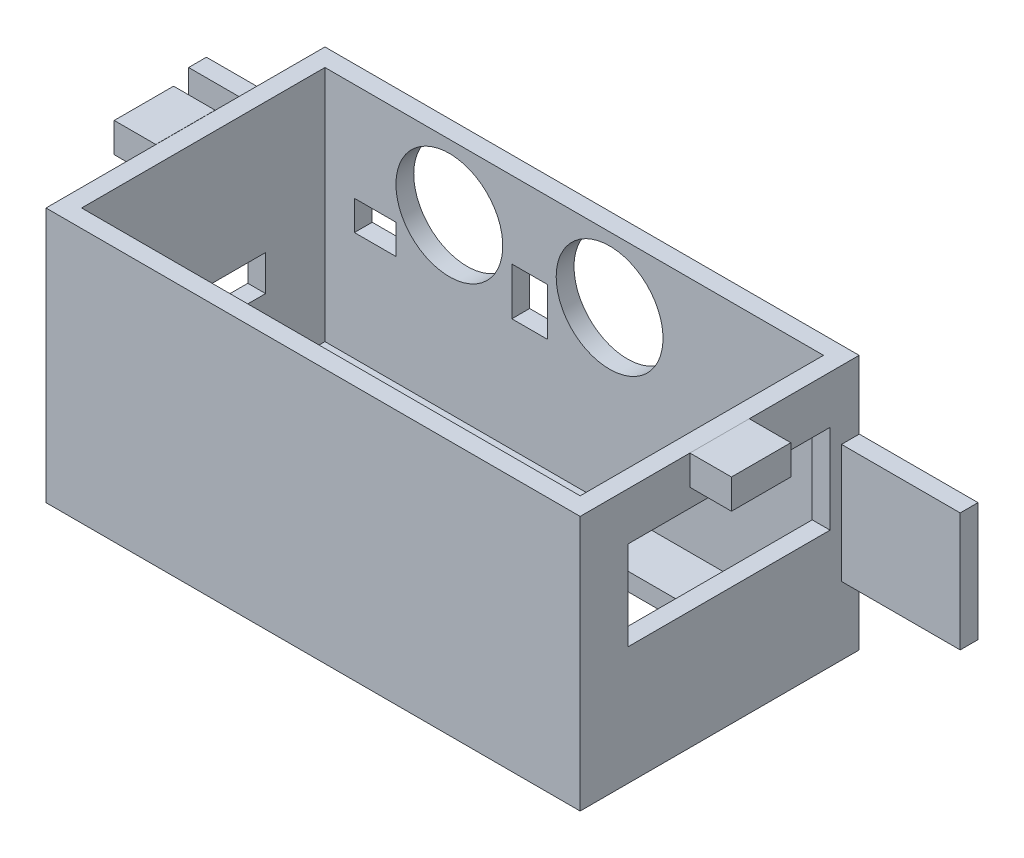
SolidWorks part; units mm, degrees
ref_plane "Alzado" through (0, 0, 0) normal (0, 0, 1) x (1, 0, 0)
ref_plane "Planta" through (0, 0, 0) normal (0, 1, 0) x (1, 0, 0)
ref_plane "Vista lateral" through (0, 0, 0) normal (1, 0, 0) x (0, 0, -1)
sketch "Croquis1" plane through (0, 0, 0) normal (0, 1, 0) x (1, 0, 0)
  line L1 (-45, 23.5) -> (45, 23.5)
  line L2 (-45, 23.5) -> (-45, -23.5)
  line L3 (-45, -23.5) -> (45, -23.5)
  line L4 (45, 23.5) -> (45, -23.5)
  line L5 (-45, 23.5) -> (45, -23.5) construction
  line L6 (-45, -23.5) -> (45, 23.5) construction
  point P0 (0, 0)
extrude "Saliente-Extruir1" add sketch "Croquis1" along normal blind 3
sketch "Croquis2" plane through (0, 3, 0) normal (0, 1, 0) x (1, 0, 0)
  line L1 (-42, 20.5) -> (42, 20.5)
  line L2 (-42, 20.5) -> (-42, -20.5)
  line L3 (-42, -20.5) -> (42, -20.5)
  line L4 (42, 20.5) -> (42, -20.5)
  line L5 (-42, 20.5) -> (42, -20.5) construction
  line L6 (-42, -20.5) -> (42, 20.5) construction
  line L9 (45, 23.5) -> (-45, 23.5) construction
  line L10 (-45, 23.5) -> (-45, -23.5) construction
  line L11 (45, -23.5) -> (45, 23.5) construction
  line L12 (-45, -23.5) -> (45, -23.5) construction
  line L13 (45, 23.5) -> (-45, 23.5)
  line L14 (-45, 23.5) -> (-45, -23.5)
  line L15 (45, -23.5) -> (45, 23.5)
  line L16 (-45, -23.5) -> (45, -23.5)
  point P0 (0, 0)
extrude "Saliente-Extruir2" add sketch "Croquis2" along normal blind 40
sketch "Croquis6" plane through (0, 0, 0) normal (0, -1, 0) x (-1, 0, 0)
  line L1 (36.0091, -12.4705) -> (-35.9909, -12.4705)
  line L2 (36.0091, -12.4705) -> (36.0091, 12.5295)
  line L3 (36.0091, 12.5295) -> (-35.9909, 12.5295)
  line L4 (-35.9909, -12.4705) -> (-35.9909, 12.5295)
extrude "Cortar-Extruir5" cut sketch "Croquis6" against normal blind 3
sketch "Croquis8" plane through (45, 0, 0) normal (1, 0, 0) x (0, 0, -1)
  line L5 (-15.4013, 34.9423) -> (18.5987, 34.9423)
  line L6 (-15.4013, 34.9423) -> (-15.4013, 19.9423)
  line L7 (-15.4013, 19.9423) -> (18.5987, 19.9423)
  line L8 (18.5987, 34.9423) -> (18.5987, 19.9423)
extrude "Cortar-Extruir6" cut sketch "Croquis8" against normal blind 3
sketch "Croquis9" plane through (45, 0, 0) normal (1, 0, 0) x (0, 0, -1)
  line L2 (-5.0086, 43.0022) -> (4.9914, 43.0022)
  line L3 (-5.0086, 43.0022) -> (-5.0086, 38.0022)
  line L4 (-5.0086, 38.0022) -> (4.9914, 38.0022)
  line L5 (4.9914, 43.0022) -> (4.9914, 38.0022)
extrude "Saliente-Extruir3" add sketch "Croquis9" along normal blind 7
sketch "Croquis10" plane through (45, 0, 0) normal (1, 0, 0) x (0, 0, -1)
  line L2 (20.5283, 31.4936) -> (23.5283, 31.4936)
  line L3 (20.5283, 31.4936) -> (20.5283, 11.4936)
  line L4 (20.5283, 11.4936) -> (23.5283, 11.4936)
  line L5 (23.5283, 31.4936) -> (23.5283, 11.4936)
extrude "Saliente-Extruir4" add sketch "Croquis10" along normal blind 20
sketch "Croquis12" plane through (-45, 0, 0) normal (-1, 0, 0) x (0, 0, 1)
  line L1 (-23.5294, 31.4856) -> (-20.5294, 31.4856)
  line L2 (-23.5294, 31.4856) -> (-23.5294, 11.4856)
  line L3 (-23.5294, 11.4856) -> (-20.5294, 11.4856)
  line L4 (-20.5294, 31.4856) -> (-20.5294, 11.4856)
extrude "Saliente-Extruir5" add sketch "Croquis12" along normal blind 20
sketch "Croquis13" plane through (-45, 0, 0) normal (-1, 0, 0) x (0, 0, 1)
  line L2 (-4.9927, 43.0287) -> (5.0073, 43.0287)
  line L3 (-4.9927, 43.0287) -> (-4.9927, 38.0287)
  line L4 (-4.9927, 38.0287) -> (5.0073, 38.0287)
  line L5 (5.0073, 43.0287) -> (5.0073, 38.0287)
extrude "Saliente-Extruir6" add sketch "Croquis13" along normal blind 7
sketch "Croquis14" plane through (-45, 0, 0) normal (-1, 0, 0) x (0, 0, 1)
  line L1 (-10.5011, 21.0075) -> (0.4989, 21.0075)
  line L2 (-10.5011, 21.0075) -> (-10.5011, 15.0075)
  line L3 (-10.5011, 15.0075) -> (0.4989, 15.0075)
  line L4 (0.4989, 21.0075) -> (0.4989, 15.0075)
  line L5 (-23.5, 43) -> (-23.5, 31.4856) construction
extrude "Cortar-Extruir8" cut sketch "Croquis14" against normal blind 3
sketch "Croquis15" plane through (0, 0, -23.5) normal (0, 0, -1) x (-1, 0, 0)
  line L14 (30.0381, 26.3981) -> (37.0381, 26.3981)
  line L15 (30.0381, 26.3981) -> (30.0381, 21.3981)
  line L16 (30.0381, 21.3981) -> (37.0381, 21.3981)
  line L17 (37.0381, 26.3981) -> (37.0381, 21.3981)
  line L20 (4.5108, 30.0753) -> (10.5108, 30.0753)
  line L21 (4.5108, 30.0753) -> (4.5108, 22.0753)
  line L22 (4.5108, 22.0753) -> (10.5108, 22.0753)
  line L23 (10.5108, 30.0753) -> (10.5108, 22.0753)
  circle A0 centre (-5.9583, 31.9461) radius 9
  circle A1 centre (21.0417, 31.9461) radius 9
  dimension "D1" = 5
extrude "Cortar-Extruir9" cut sketch "Croquis15" against normal blind 3
